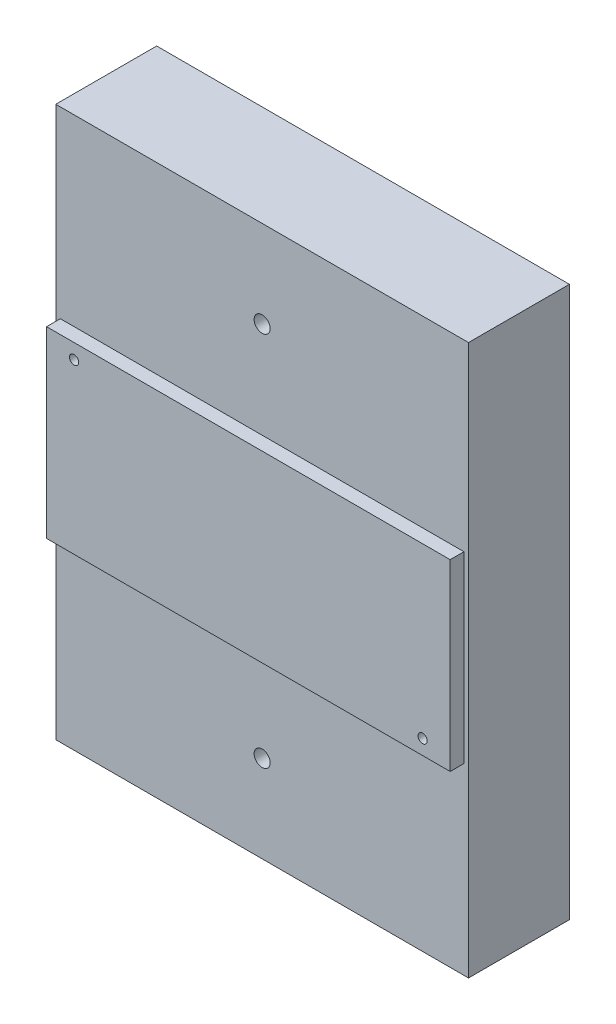
SolidWorks part; units mm, degrees
ref_plane "Front Plane" through (0, 0, 0) normal (0, 0, 1) x (1, 0, 0)
ref_plane "Top Plane" through (0, 0, 0) normal (0, 1, 0) x (1, 0, 0)
ref_plane "Right Plane" through (0, 0, 0) normal (1, 0, 0) x (0, 0, -1)
sketch "Sketch1" plane through (0, 0, 0) normal (0, 0, 1) x (1, 0, 0)
  line L0 (0, 60) -> (0, -60) construction
  line L5 (-45, 60) -> (45, 60)
  line L6 (-45, 60) -> (-45, -60)
  line L7 (-45, -60) -> (45, -60)
  line L8 (45, 60) -> (45, -60)
  line L9 (-45, 0) -> (45, 0) construction
  circle A0 centre (0, 41) radius 1.75
  circle A1 centre (0, -41) radius 1.75
  point P13 (0, 0)
  point P14 (0, 0)
  dimension "D2" = 3.5
  dimension "D1" = 82
  dimension "D3" = 90
  dimension "D4" = 120
extrude "Boss-Extrude1" add sketch "Sketch1" along normal blind 22
sketch "Sketch3" plane through (0, 0, 0) normal (0, 0, 1) x (1, 0, 0)
  line L0 (-44, -20) -> (-44, 20)
  line L1 (-44, -20) -> (44, -20)
  line L2 (44, -20) -> (44, 20)
  line L3 (-44, 20) -> (44, 20)
  line L4 (-44, 0) -> (44, 0) construction
  line L5 (0, 20) -> (0, -20) construction
  line L6 (-38, 16.75) -> (-38, 0) construction
  line L7 (38, -16.75) -> (38, 0) construction
  line L8 (-38, 16.75) -> (0, 16.75) construction
  line L9 (38, -16.75) -> (0, -16.75) construction
  circle A3 centre (-38, 16.75) radius 1
  circle A4 centre (38, -16.75) radius 1
  dimension "D5" = 2
  dimension "D1" = 88
  dimension "D2" = 40
  dimension "D3" = 76
  dimension "D4" = 33.5
extrude "Boss-Extrude2" add sketch "Sketch3" along normal blind 25
